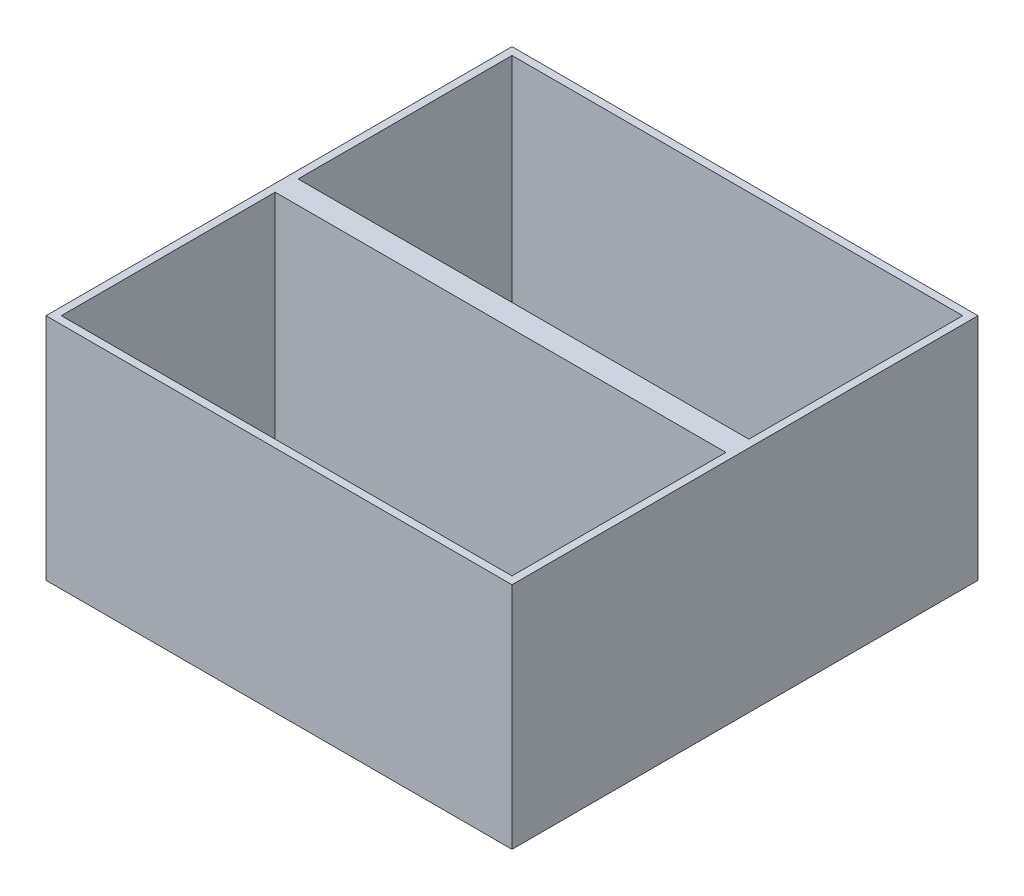
SolidWorks part; units mm, degrees
ref_plane "前视基准面" through (0, 0, 0) normal (0, 0, 1) x (1, 0, 0)
ref_plane "上视基准面" through (0, 0, 0) normal (0, 1, 0) x (1, 0, 0)
ref_plane "右视基准面" through (0, 0, 0) normal (1, 0, 0) x (0, 0, -1)
sketch "草图1" plane through (0, 0, 0) normal (0, 1, 0) x (1, 0, 0)
  line L1 (0, 0) -> (300, 0)
  line L2 (0, 0) -> (0, 300)
  line L3 (0, 300) -> (300, 300)
  line L4 (300, 0) -> (300, 300)
  dimension "D1" = 300
  dimension "D2" = 300
extrude "拉伸-薄壁1" add sketch "草图1" along normal blind 150 thin thin type mid plane wall 5
sketch "草图2" plane through (0, 0, 0) normal (0, 1, 0) x (1, 0, 0)
  line L0 (2.5, 150) -> (297.5, 150)
  line L1 (2.5, 297.5) -> (2.5, 2.5) construction
  line L2 (297.5, 2.5) -> (297.5, 297.5) construction
extrude "拉伸-薄壁2" add sketch "草图2" along normal up to surface (150 mm away) thin up to face at (150, 150, -150) thin type mid plane wall 15
